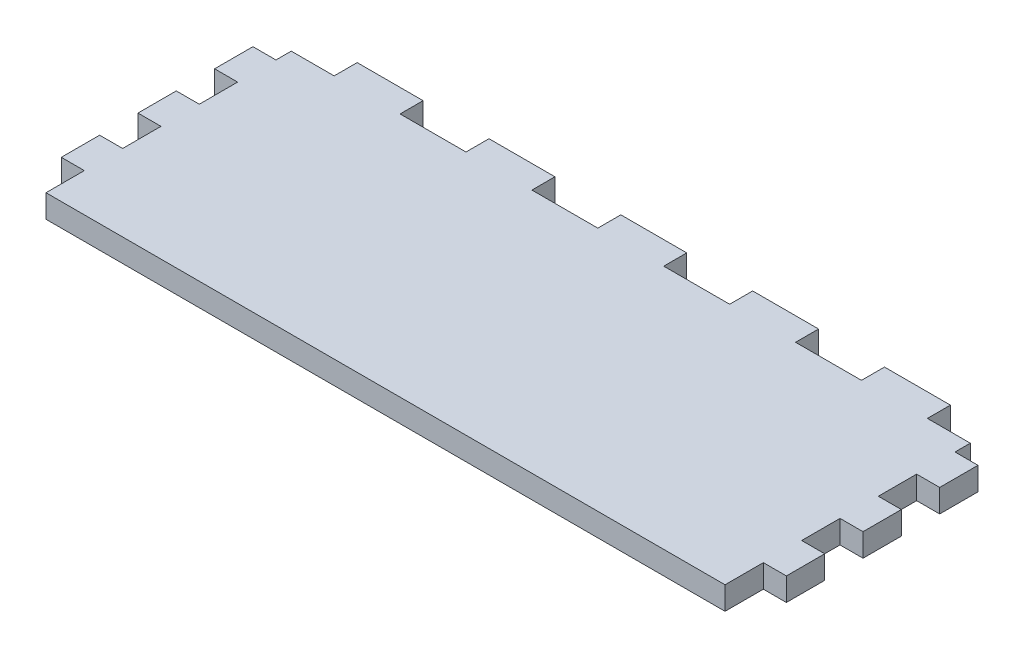
SolidWorks part; units mm, degrees
material "Pin"
ref_plane "Plan de face" through (0, 0, 0) normal (0, 0, 1) x (1, 0, 0)
ref_plane "Plan de dessus" through (0, 0, 0) normal (0, 1, 0) x (1, 0, 0)
ref_plane "Plan de droite" through (0, 0, 0) normal (1, 0, 0) x (0, 0, -1)
sketch "Esquisse1" plane through (0, 0, 0) normal (0, 1, 0) x (1, 0, 0)
  line L1 (-100, 0) -> (100, 0)
  line L2 (-100, 0) -> (-100, 74)
  line L3 (-100, 74) -> (100, 74)
  line L4 (100, 0) -> (100, 74)
  point P4 (0, 0)
  dimension "D1" = 200
  dimension "D2" = 74
extrude "Boss.-Extru.1" add sketch "Esquisse1" along normal blind 6.35
sketch "Esquisse2" plane through (0, 6.35, 0) normal (0, 1, 0) x (1, 0, 0)
  line L0 (100, 0) -> (100, 74) construction
  line L1 (100, 74) -> (93.65, 74)
  line L2 (100, 74) -> (100, 63.4286)
  line L3 (100, 63.4286) -> (93.65, 63.4286)
  line L4 (93.65, 74) -> (93.65, 63.4286)
  line L5 (100, 52.8571) -> (93.65, 52.8571)
  line L6 (100, 52.8571) -> (100, 42.2857)
  line L7 (100, 42.2857) -> (93.65, 42.2857)
  line L8 (93.65, 52.8571) -> (93.65, 42.2857)
  line L9 (93.65, 52.8571) -> (93.65, 63.4286) construction
  line L10 (100, 31.7143) -> (93.65, 31.7143)
  line L11 (100, 31.7143) -> (100, 21.1429)
  line L12 (100, 21.1429) -> (93.65, 21.1429)
  line L13 (93.65, 31.7143) -> (93.65, 21.1429)
  line L14 (100, 10.5714) -> (93.65, 10.5714)
  line L15 (100, 10.5714) -> (100, 0)
  line L16 (100, 0) -> (93.65, 0)
  line L17 (93.65, 10.5714) -> (93.65, 0)
  line L18 (93.65, 42.2857) -> (93.65, 31.7143) construction
  line L19 (93.65, 21.1429) -> (93.65, 10.5714) construction
  dimension "D1" = 6.35
extrude "Enlèv. mat.-Extru.1" cut sketch "Esquisse2" against normal blind 6.35
mirror "Symétrie1" about plane through (0, 0, 0) normal (1, 0, 0) of "Enlèv. mat.-Extru.1"
sketch "Esquisse3" plane through (0, 6.35, 0) normal (0, 1, 0) x (1, 0, 0)
  line L0 (93.65, 74) -> (-93.65, 74) construction
  line L1 (-81.8182, 74) -> (-100, 74)
  line L2 (-81.8182, 74) -> (-81.8182, 67.65)
  line L3 (-81.8182, 67.65) -> (-100, 67.65)
  line L4 (-100, 74) -> (-100, 67.65)
  line L5 (-81.8182, 67.65) -> (-63.6364, 67.65) construction
  line L6 (-63.6364, 74) -> (-45.4545, 74)
  line L7 (-63.6364, 74) -> (-63.6364, 67.65)
  line L8 (-63.6364, 67.65) -> (-45.4545, 67.65)
  line L9 (-45.4545, 74) -> (-45.4545, 67.65)
  line L10 (-27.2727, 74) -> (-9.0909, 74)
  line L11 (-27.2727, 74) -> (-27.2727, 67.65)
  line L12 (-27.2727, 67.65) -> (-9.0909, 67.65)
  line L13 (-9.0909, 74) -> (-9.0909, 67.65)
  line L14 (9.0909, 74) -> (27.2727, 74)
  line L15 (9.0909, 74) -> (9.0909, 67.65)
  line L16 (9.0909, 67.65) -> (27.2727, 67.65)
  line L17 (27.2727, 74) -> (27.2727, 67.65)
  line L18 (45.4545, 74) -> (63.6364, 74)
  line L19 (45.4545, 74) -> (45.4545, 67.65)
  line L20 (45.4545, 67.65) -> (63.6364, 67.65)
  line L21 (63.6364, 74) -> (63.6364, 67.65)
  line L22 (81.8182, 74) -> (100, 74)
  line L23 (81.8182, 74) -> (81.8182, 67.65)
  line L24 (81.8182, 67.65) -> (100, 67.65)
  line L25 (100, 74) -> (100, 67.65)
  line L26 (-45.4545, 67.65) -> (-27.2727, 67.65) construction
  line L27 (-9.0909, 67.65) -> (9.0909, 67.65) construction
  line L28 (27.2727, 67.65) -> (45.4545, 67.65) construction
  line L29 (63.6364, 67.65) -> (81.8182, 67.65) construction
  line L30 (-100, 63.4286) -> (-100, 52.8571) construction
  line L31 (100, 52.8571) -> (100, 63.4286) construction
  dimension "D1" = 6.35
extrude "Enlèv. mat.-Extru.2" cut sketch "Esquisse3" against normal blind 6.35
